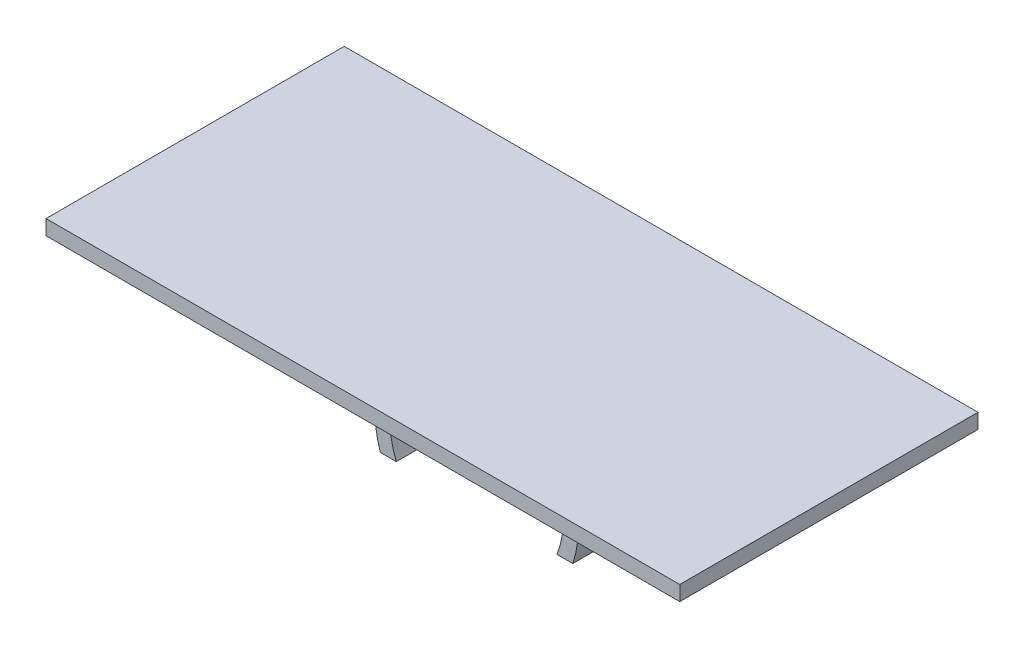
SolidWorks part; units mm, degrees
ref_plane "Front" through (0, 0, 0) normal (0, 0, 1) x (1, 0, 0)
ref_plane "Top" through (0, 0, 0) normal (0, 1, 0) x (1, 0, 0)
ref_plane "Right" through (0, 0, 0) normal (1, 0, 0) x (0, 0, -1)
sketch "Sketch1" plane through (0, 0, 0) normal (0, 0, 1) x (1, 0, 0)
  circle A0 centre (0, 0) radius 9.125
  circle A1 centre (0, 0) radius 11.125
  dimension "D1" = 18.25
  dimension "D2" = 2
extrude "Boss-Extrude1" add sketch "Sketch1" along normal blind 10
sketch "Sketch2" plane through (0, 0, 10) normal (0, 0, 1) x (1, 0, 0)
  line L0 (9.125, -11.125) -> (9.125, -9.125)
  line L1 (9.125, -11.125) -> (-9.125, -11.125)
  line L2 (0, -11.125) -> (0, -9.125)
  line L3 (9.125, -9.125) -> (-9.125, -9.125)
  line L4 (-9.125, -11.125) -> (-9.125, -9.125)
  line L5 (-9.125, -9.125) -> (-9.125, -6.364)
  line L6 (-9.125, -6.364) -> (-4.6463, -9.125)
  line L7 (-4.6463, -9.125) -> (4.4394, -9.125)
  line L8 (4.4394, -9.125) -> (9.125, -6.364)
  line L9 (9.125, -6.364) -> (9.125, -9.125)
  circle A1 centre (0, 0) radius 11.125 construction
  circle M3 centre (0, 0) radius 11.125
extrude "Boss-Extrude2" add sketch "Sketch2" against normal up to surface (10 mm away) contours L5 L3 M3 | L4 L1 L3 M3 | L0 L3 L1 M3 | L9 L3 M3 up to face at (11.125, 0, 0)
sketch "Sketch3" plane through (0, 0, 10) normal (0, 0, 1) x (1, 0, 0)
  line L0 (12.9035, -4.375) -> (10.7703, -4.375)
  line L1 (-10.7703, -4.375) -> (-12.9035, -4.375)
  line L2 (16.5076, 13.625) -> (42.5, 13.625)
  line L3 (-42.5, 15.625) -> (42.5, 15.625)
  line L4 (-42.5, 15.625) -> (-42.5, 13.625)
  line L5 (-42.5, 13.625) -> (-16.5076, 13.625)
  line L6 (42.5, 15.625) -> (42.5, 13.625)
  arc A0 (10.7703, -4.375) -> (-10.7703, -4.375) centre (0, 0) ccw
  arc A1 (12.9035, -4.375) -> (12.076, 6.3096) centre (0, 0) ccw
  arc A2 (9.125, -6.364) -> (-9.125, -6.364) centre (0, 0) ccw construction
  arc A3 (16.5076, 13.625) -> (12.076, 6.3096) centre (16.5076, 8.625) ccw
  arc A4 (-12.076, 6.3096) -> (-16.5076, 13.625) centre (-16.5076, 8.625) ccw
  arc A5 (-12.076, 6.3096) -> (-12.9035, -4.375) centre (0, 0) ccw
  point P14 (0, 15.625)
  point P18 (-16.5771, 8.5828)
  dimension "D1" = 0.5
  dimension "D2" = 2
  dimension "D6" = 10
  dimension "D7" = 10
  dimension "D3" = 18
  dimension "D4" = 85
  dimension "D5" = 2
extrude "Boss-Extrude3" add sketch "Sketch3" along normal blind 40 separate body
sketch "Sketch4" plane through (0, 13.625, 0) normal (0, -1, 0) x (1, 0, 0)
  line L0 (16.5076, 50) -> (42.5, 50) construction
  line L1 (-27.0164, 34.75) -> (30.6708, 34.75)
  line L2 (-27.0164, 34.75) -> (-27.0164, 50)
  line L3 (-27.0164, 50) -> (30.6708, 50)
  line L4 (30.6708, 34.75) -> (30.6708, 50)
  line L5 (16.5076, 10) -> (42.5, 10) construction
  line L6 (27.2774, 10) -> (-27.0164, 10)
  line L7 (27.2774, 10) -> (27.2774, 25.25)
  line L8 (27.2774, 25.25) -> (-27.0164, 25.25)
  line L9 (-27.0164, 10) -> (-27.0164, 25.25)
  dimension "D1" = 9.5
extrude "Cut-Extrude1" cut sketch "Sketch4" along normal blind 42
sketch "Sketch5" plane through (0, 13.625, 0) normal (0, -1, 0) x (1, 0, 0)
  line L1 (-25.3197, 15.5377) -> (27.7995, 15.5377)
  line L2 (-25.3197, 15.5377) -> (-25.3197, -11.3481)
  line L3 (-25.3197, -11.3481) -> (27.7995, -11.3481)
  line L4 (27.7995, 15.5377) -> (27.7995, -11.3481)
extrude "Cut-Extrude2" cut sketch "Sketch5" along normal blind 61
